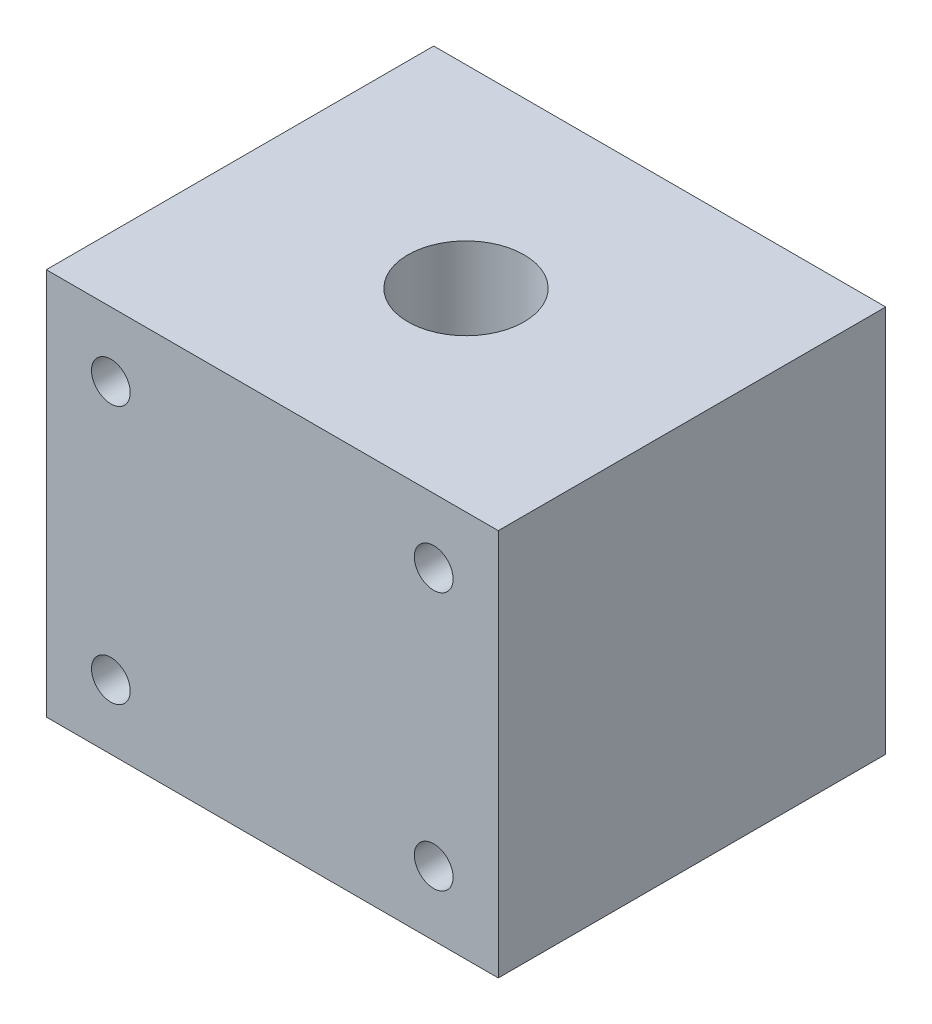
SolidWorks part; units mm, degrees
ref_plane "Front Plane" through (0, 0, 0) normal (0, 0, 1) x (1, 0, 0)
ref_plane "Top Plane" through (0, 0, 0) normal (0, 1, 0) x (1, 0, 0)
ref_plane "Right Plane" through (0, 0, 0) normal (1, 0, 0) x (0, 0, -1)
sketch "Sketch1" plane through (0, 0, 0) normal (0, 1, 0) x (1, 0, 0)
  line L1 (-17.5, -15) -> (17.5, -15)
  line L2 (-17.5, -15) -> (-17.5, 15)
  line L3 (-17.5, 15) -> (17.5, 15)
  line L4 (17.5, -15) -> (17.5, 15)
  line L5 (-17.5, -15) -> (17.5, 15) construction
  line L6 (-17.5, 15) -> (17.5, -15) construction
  point P0 (0, 0)
  dimension "D1" = 35
  dimension "D2" = 30
extrude "Boss-Extrude1" add sketch "Sketch1" along normal blind 30
sketch "Sketch2" plane through (0, 0, 15) normal (0, 0, 1) x (1, 0, 0)
  line L0 (-17.5, 30) -> (17.5, 30) construction
  line L1 (-17.5, 30) -> (-17.5, 0) construction
  line L2 (17.5, 30) -> (17.5, 0) construction
  line L3 (-17.5, 0) -> (17.5, 0) construction
  circle A0 centre (-12.5, 25) radius 1.5
  circle A1 centre (12.5, 25) radius 1.5
  circle A2 centre (12.5, 5) radius 1.5
  circle A3 centre (-12.5, 5) radius 1.5
  dimension "D1" = 3
  dimension "D4" = 5
  dimension "D2" = 5
  dimension "D3" = 5
  dimension "D5" = 5
  dimension "D6" = 5
  dimension "D7" = 5
  dimension "D8" = 5
  dimension "D9" = 5
extrude "Cut-Extrude1" cut sketch "Sketch2" against normal blind 10
sketch "Sketch5" plane through (0, 0, 0) normal (0, -1, 0) x (1, 0, 0)
  circle A0 centre (0, 0) radius 11
  dimension "D1" = 22
extrude "Cut-Extrude4" cut sketch "Sketch5" against normal blind 3
sketch "Sketch6" plane through (0, 3, 0) normal (0, -1, 0) x (-1, 0, 0)
  circle A0 centre (0, 0) radius 4.5
  dimension "9" = 9
extrude "Cut-Extrude5" cut sketch "Sketch6" along normal through all both and the other way through all
